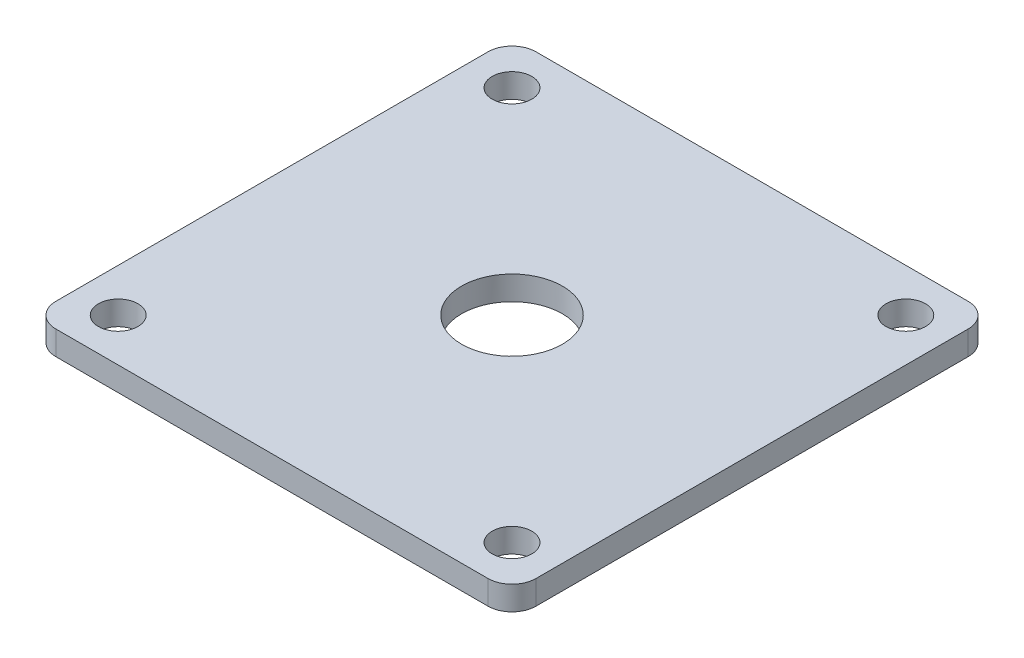
SolidWorks part; units mm, degrees
ref_plane "Front" through (0, 0, 0) normal (0, 0, 1) x (1, 0, 0)
ref_plane "Top" through (0, 0, 0) normal (0, 1, 0) x (1, 0, 0)
ref_plane "Right" through (0, 0, 0) normal (1, 0, 0) x (0, 0, -1)
sketch "Sketch1" plane through (0, 0, 0) normal (0, 1, 0) x (1, 0, 0)
  line L1 (-31.75, -31.75) -> (31.75, -31.75)
  line L2 (-31.75, -31.75) -> (-31.75, 31.75)
  line L3 (-31.75, 31.75) -> (31.75, 31.75)
  line L4 (31.75, -31.75) -> (31.75, 31.75)
  line L5 (-31.75, -31.75) -> (31.75, 31.75) construction
  line L6 (-31.75, 31.75) -> (31.75, -31.75) construction
  point P0 (0, 0)
  dimension "D1" = 63.5
  dimension "D2" = 63.5
extrude "Boss-Extrude1" add sketch "Sketch1" along normal blind 3.175
fillet "Fillet1" radius 3.175 4 edges at (31.75, 1.5875, -31.75) (-31.75, 1.5875, -31.75) (-31.75, 1.5875, 31.75) (31.75, 1.5875, 31.75)
sketch "Sketch2" plane through (0, 3.175, 0) normal (0, 1, 0) x (1, 0, 0)
  circle A0 centre (0, 0) radius 6.6675
  dimension "D1" = 13.335
extrude "Cut-Extrude1" cut sketch "Sketch2" against normal up to next
sketch "Sketch3" plane through (0, 3.175, 0) normal (0, 1, 0) x (1, 0, 0)
  line L0 (31.75, 0) -> (-31.75, 0) construction
  line L1 (31.75, -28.575) -> (31.75, 28.575) construction
  line L2 (-31.75, 28.575) -> (-31.75, -28.575) construction
  circle A2 centre (26.0427, -26.0427) radius 2.6162 construction
  circle A3 centre (-26.0427, -26.0427) radius 2.6162 construction
  circle A6 centre (26.0427, -26.0427) radius 2.6162
  circle A7 centre (-26.0427, -26.0427) radius 2.6162
  circle A8 centre (26.0427, 26.0427) radius 2.6162
  circle A9 centre (-26.0427, 26.0427) radius 2.6162
extrude "Cut-Extrude2" cut sketch "Sketch3" against normal up to next
